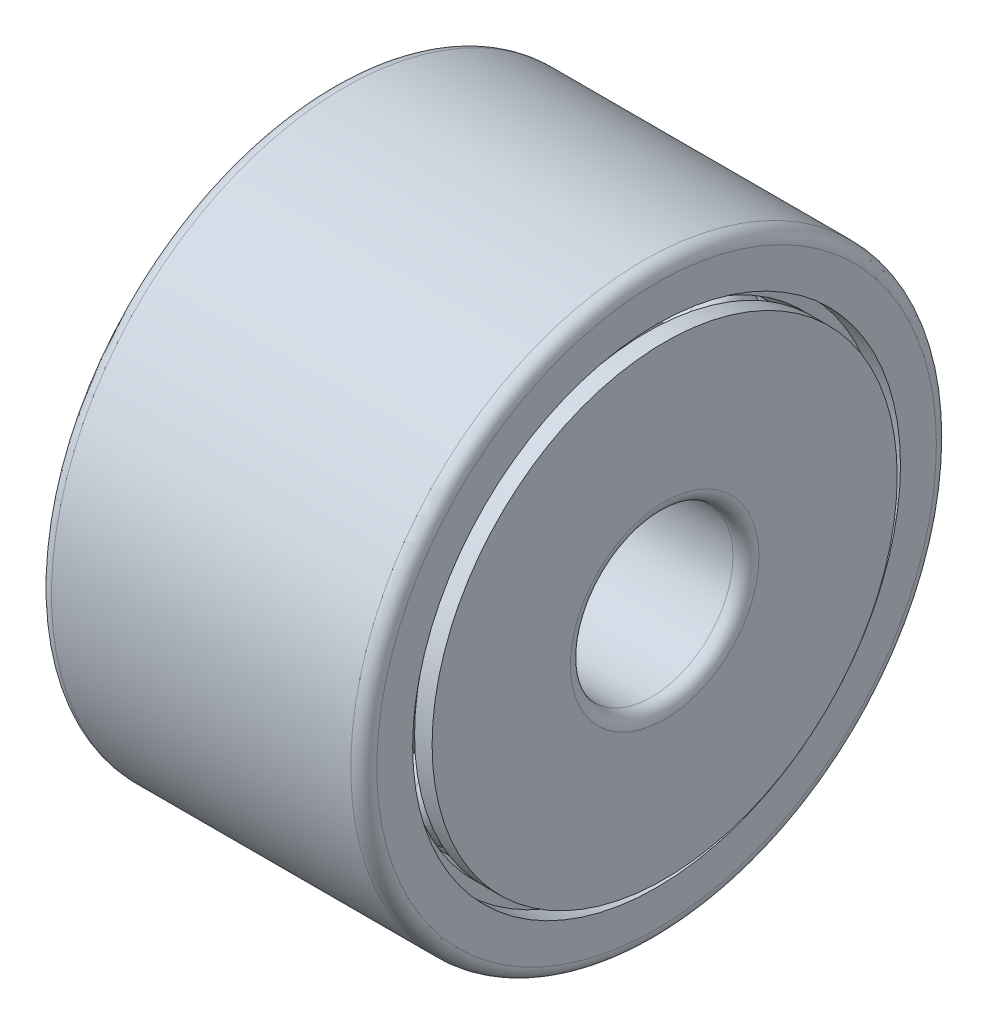
SolidWorks part; units mm, degrees
ref_plane "Plane1" through (0, 0, 0) normal (0, 0, 1) x (1, 0, 0)
ref_plane "Plane2" through (0, 0, 0) normal (0, 1, 0) x (1, 0, 0)
ref_plane "Plane3" through (0, 0, 0) normal (1, 0, 0) x (0, 0, -1)
sketch "Clipboard" plane through (0, 0, 0) normal (0, 0, 1) x (1, 0, 0)
  line L0 (-10, 0) -> (10, 0) construction
  line L1 (0, 0) -> (27.0344, -5.7463)
  line L2 (0, 0) -> (22.4793, 28.7722)
  line L3 (0, 0) -> (27.9428, -35.7651)
  line L4 (0, 0) -> (-22.3471, -0.7804)
  dimension "Race_OD" = 45.3866
  dimension "CLdia" = 36.5125
  dimension "Count" = 52
  dimension "Show_count" = 52
  dimension "Max_count" = 12
  dimension "Min_count" = 2
  dimension "Race_ID" = 27.6384
sketch "OutRacSke" plane through (0, 0, 0) normal (0, 0, 1) x (1, 0, 0)
  line L0 (-14.0229, 22.6933) -> (-14.0229, 23.8026)
  line L1 (-14.0229, 23.8026) -> (-15.875, 23.8026)
  line L2 (-15.875, 23.8026) -> (-15.875, 27.305)
  line L3 (-14.605, 28.575) -> (14.605, 28.575)
  line L4 (15.875, 27.305) -> (15.875, 23.8026)
  line L5 (15.875, 23.8026) -> (14.0229, 23.8026)
  line L6 (14.0229, 23.8026) -> (14.0229, 22.6933)
  line L7 (14.0229, 22.6933) -> (-14.0229, 22.6933)
  line L8 (-7.9375, 0) -> (7.9375, 0) construction
  arc A0 (-15.875, 27.305) -> (-14.605, 28.575) centre (-14.605, 27.305) cw
  arc A1 (14.605, 28.575) -> (15.875, 27.305) centre (14.605, 27.305) cw
  dimension "Radius" = 1.27
  dimension "Race_OD" = 45.3866
  dimension "OD" = 57.15
  dimension "Cyl_Len" = 28.0458
  dimension "Width" = 31.75
  dimension "Groove_Dp" = 1.1093
  dimension "halfWidth" = 15.875
  dimension "D1" = 14.0229
revolve "OuterRace" add sketch "OutRacSke" angle 360 about L8
sketch "RolDetSke" plane through (0, 0, 0) normal (0, 0, 1) x (1, 0, 0)
  line L0 (-14.0229, 20.9261) -> (-14.0229, 18.2562)
  line L1 (-14.0229, 18.2562) -> (14.0229, 18.2562)
  line L2 (14.0229, 18.2562) -> (14.0229, 20.9261)
  line L3 (12.243, 22.706) -> (-12.243, 22.706)
  line L4 (-28.575, 18.2562) -> (28.575, 18.2562) construction
  arc A0 (14.0229, 20.9261) -> (12.243, 22.706) centre (12.243, 20.9261) ccw
  arc A1 (-12.243, 22.706) -> (-14.0229, 20.9261) centre (-12.243, 20.9261) ccw
  dimension "Cyl_Len" = 28.0458
  dimension "radius" = 1.7799
  dimension "CLRad" = 18.2562
  dimension "Roller_diameter" = 8.8995
  dimension "halfCylLen" = 14.0229
revolve "RollerDetailed" add sketch "RolDetSke" angle 360 about L4
ref_axis "Axis1" through (-50, 0, 0) along (1, 0, 0)
pattern_circular "RollersDetailed" count 12 every 30 about axis through (-50, 0, 0) along (1, 0, 0) of "RollerDetailed"
sketch "RolSimSke" plane through (0, 25.4, 0) normal (0, 0, 1) x (1, 0, 0)
  line L0 (-14.0229, -4.4612) -> (-14.0229, -9.8009)
  line L1 (-25.4, -25.4) -> (25.4, -25.4) construction
  line L2 (14.0229, -9.8009) -> (14.0229, -4.4612)
  line L3 (12.243, -2.6813) -> (-12.243, -2.6813)
  line L5 (12.243, -11.5808) -> (-12.243, -11.5808)
  arc A0 (14.0229, -4.4612) -> (12.243, -2.6813) centre (12.243, -4.4612) ccw
  arc A1 (-12.243, -2.6813) -> (-14.0229, -4.4612) centre (-12.243, -4.4612) ccw
  arc A2 (14.0229, -9.8009) -> (12.243, -11.5808) centre (12.243, -9.8009) cw
  arc A3 (-12.243, -11.5808) -> (-14.0229, -9.8009) centre (-12.243, -9.8009) cw
  dimension "radius" = 1.7799
  dimension "Roller_diameter" = 8.8995
  dimension "Bore" = 27.6384
  dimension "Cyl_Len" = 28.0458
  dimension "halfLength" = 14.0229
revolve "RollersSimplified" [suppressed] add sketch "RolSimSke" angle 360 about L1
sketch "InsRacSke" plane through (0, 0, 0) normal (0, 0, 1) x (1, 0, 0)
  line L0 (-14.949, 13.8192) -> (-14.949, 22.6933)
  line L1 (-14.949, 22.6933) -> (-16.6624, 22.6933)
  line L2 (-16.6624, 22.6933) -> (-16.6624, 9.2075)
  line L3 (-15.3924, 7.9375) -> (-0.84, 7.9375)
  line L4 (0.84, 7.9375) -> (15.3924, 7.9375)
  line L5 (16.6624, 9.2075) -> (16.6624, 22.6933)
  line L6 (16.6624, 22.6933) -> (14.949, 22.6933)
  line L7 (14.949, 22.6933) -> (14.949, 13.8192)
  line L8 (14.949, 13.8192) -> (-14.949, 13.8192)
  line L9 (-7.9375, 0) -> (7.9375, 0) construction
  arc A0 (-16.6624, 9.2075) -> (-15.3924, 7.9375) centre (-15.3924, 9.2075) ccw
  arc A1 (-0.84, 7.9375) -> (0.84, 7.9375) centre (0, 6.985) cw
  arc A2 (15.3924, 7.9375) -> (16.6624, 9.2075) centre (15.3924, 9.2075) ccw
  dimension "Race_ID" = 27.6384
  dimension "radius" = 1.27
  dimension "Bore" = 15.875
  dimension "Width_IR" = 33.3248
  dimension "halfWidth" = 16.6624
  dimension "Race_OD" = 45.3866
  dimension "offset" = 0.9525
  dimension "SlotWidth" = 29.8979
  dimension "halfSlotWidth" = 14.949
revolve "InnerRace" add sketch "InsRacSke" angle 360 about L9
equation "\"halfWidth@OutRacSke\" =  \"Width@OutRacSke\" / 2"
equation "\"CLdia@Clipboard\" =  ( \"Race_OD@Clipboard\" + \"Race_ID@Clipboard\" )  / 2"
equation "\"CLRad@RolDetSke\" = ( \"Race_OD@Clipboard\" + \"Race_ID@Clipboard\" )  / 4"
equation "\"Roller_diameter@RolDetSke\" =  ( \"Race_OD@Clipboard\" -  \"Race_ID@Clipboard\" )  / 2 + .001"
equation "\"Roller_diameter@RolSimSke\" = ( \"Race_OD@Clipboard\" -  \"Race_ID@Clipboard\" )  / 2 + .001"
equation "\"radius@RolDetSke\" = \"Roller_diameter@RolDetSke\" / 5"
equation "\"radius@RolSimSke\" = \"Roller_diameter@RolSimSke\" / 5"
equation "\"Cyl_Len@OutRacSke\" = \"Cyl_Len@RolDetSke\""
equation "\"Cyl_Len@RolSimSke\" = \"Cyl_Len@RolDetSke\""
equation "\"halfCylLen@RolDetSke\" = \"Cyl_Len@RolDetSke\" / 2"
equation "\"offset@InsRacSke\" = \"radius@InsRacSke\" * 0.75"
equation "\"SlotWidth@InsRacSke\" =  ( \"Width@OutRacSke\" + \"Cyl_Len@RolDetSke\" )  / 2"
equation "\"halfSlotWidth@InsRacSke\" = \"SlotWidth@InsRacSke\" / 2"
equation "\"D1@OutRacSke\" = \"Cyl_Len@OutRacSke\" / 2"
equation "\"Max_count@Clipboard\" = int( 3.14159265 / atn(( \"Roller_diameter@RolDetSke\" / 2) / sqr( \"CLRad@RolDetSke\"  *  \"CLRad@RolDetSke\" - ( \"Roller_diameter@RolDetSke\" / 2) *  ( \"Roller_diameter@RolDetSke\" / 2))))"
equation "\"Max_count@Clipboard\" = ((sgn( \"Max_count@Clipboard\" - \"Count@Clipboard\" )-1)*( \"Max_count@Clipboard\" - \"Count@Clipboard\" ))/-2+ \"Count@Clipboard\""
equation "\"Count@RollersDetailed\" = int( \"Show_count@Clipboard\" ) "
equation "\"Count@RollersDetailed\" = ((sgn( \"Count@RollersDetailed\" - \"Max_count@Clipboard\" )-1)*( \"Count@RollersDetailed\" - \"Max_count@Clipboard\" ))/-2+ \"Max_count@Clipboard\""
equation "\"Count@RollersDetailed\" = ((sgn( \"Count@RollersDetailed\" - \"Min_count@Clipboard\" )+1)*( \"Count@RollersDetailed\" - \"Min_count@Clipboard\"))/2 +\"Min_count@Clipboard\""
equation "\"Angle@RollersDetailed\" = 360.0 / \"Max_count@Clipboard\""
equation "\"Bore@RolSimSke\" = \"Race_ID@Clipboard\""
equation "\"Race_ID@InsRacSke\" = \"Race_ID@Clipboard\""
equation "\"Race_OD@InsRacSke\" = \"Race_OD@Clipboard\""
equation "\"halfWidth@InsRacSke\" = \"Width_IR@InsRacSke\" / 2"
equation "\"halfLength@RolSimSke\" = \"Cyl_Len@RolSimSke\" / 2"
equation "\"Race_OD@OutRacSke\" = \"Race_OD@Clipboard\""
